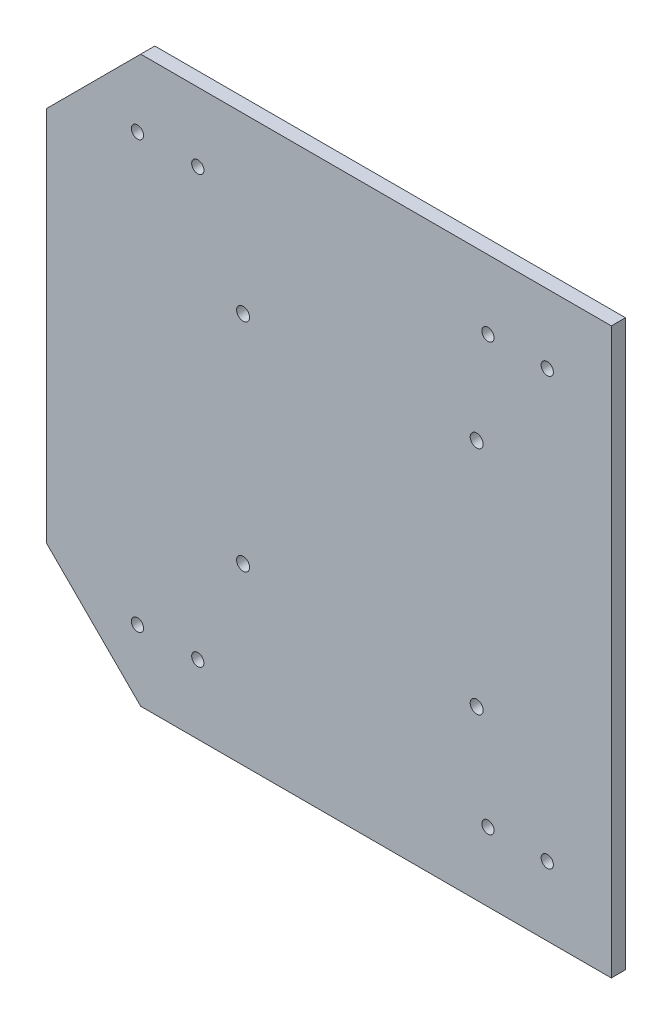
SolidWorks part; units mm, degrees
ref_plane "Front Plane" through (0, 0, 0) normal (0, 0, 1) x (1, 0, 0)
ref_plane "Top Plane" through (0, 0, 0) normal (0, 1, 0) x (1, 0, 0)
ref_plane "Right Plane" through (0, 0, 0) normal (1, 0, 0) x (0, 0, -1)
sketch "Sketch1" plane through (0, 0, 0) normal (0, 0, 1) x (1, 0, 0)
  line L0 (-107.95, -76.2) -> (-133.35, -50.8)
  line L1 (-107.95, -76.2) -> (-133.35, -50.8)
  line L2 (-133.35, -50.8) -> (-133.35, 50.8)
  line L3 (-133.35, -50.8) -> (-133.35, 50.8)
  line L4 (-133.35, 50.8) -> (-107.95, 76.2)
  line L5 (-133.35, 50.8) -> (-107.95, 76.2)
  line L6 (-107.95, 76.2) -> (19.05, 76.2)
  line L7 (-107.95, 76.2) -> (19.05, 76.2)
  line L8 (19.05, 76.2) -> (19.05, -76.2)
  line L9 (19.05, 76.2) -> (19.05, -76.2)
  line L10 (19.05, -76.2) -> (-107.95, -76.2)
  line L11 (19.05, -76.2) -> (-107.95, -76.2)
extrude "Boss-Extrude1" add sketch "Sketch1" along normal blind 3.81
sketch "Sketch2" plane through (0, 0, 3.81) normal (0, 0, 1) x (1, 0, 0)
  circle A0 centre (1.7583, 57.577) radius 1.65
  circle A1 centre (-14.2391, 57.577) radius 1.65
  circle A2 centre (-92.5422, 57.577) radius 1.65
  circle A3 centre (-108.8202, 57.577) radius 1.65
  circle A4 centre (-108.8202, -57.577) radius 1.65
  circle A5 centre (-92.5422, -57.577) radius 1.65
  circle A6 centre (-14.2391, -57.577) radius 1.65
  circle A7 centre (1.7583, -57.577) radius 1.65
  dimension "D1" = 3.3
  dimension "D2" = 3.3
  dimension "D3" = 3.3
  dimension "D4" = 3.3
  dimension "D5" = 3.3
  dimension "D6" = 3.3
  dimension "D7" = 3.3
  dimension "D8" = 3.3
extrude "Cut-Extrude1" cut sketch "Sketch2" against normal blind 8.89
sketch "Sketch3" plane through (0, 0, 3.81) normal (0, 0, 1) x (1, 0, 0)
  circle A0 centre (-80.3084, 29.3602) radius 1.75
  circle A1 centre (-17.2857, 31.2451) radius 1.75
  circle A2 centre (-17.2857, -30.9566) radius 1.75
  circle A3 centre (-80.3084, -29.0716) radius 1.75
extrude "Cut-Extrude2" cut sketch "Sketch3" against normal through all
